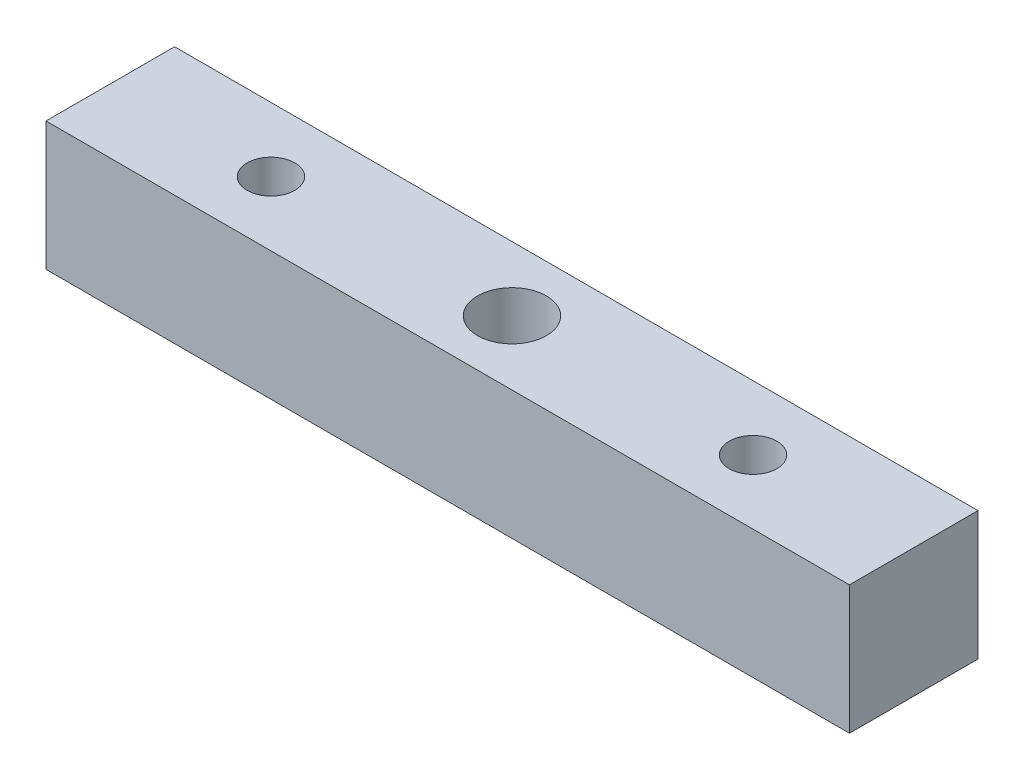
SolidWorks part; units mm, degrees
material "7075-T6 (SN)"
ref_plane "Front Plane" through (0, 0, 0) normal (0, 0, 1) x (1, 0, 0)
ref_plane "Top Plane" through (0, 0, 0) normal (0, 1, 0) x (1, 0, 0)
ref_plane "Right Plane" through (0, 0, 0) normal (1, 0, 0) x (0, 0, -1)
sketch "Sketch1" plane through (0, 0, 0) normal (0, 1, 0) x (1, 0, 0)
  line L1 (-25, 4) -> (25, 4)
  line L2 (-25, 4) -> (-25, -4)
  line L3 (-25, -4) -> (25, -4)
  line L4 (25, 4) -> (25, -4)
  line L5 (-25, 4) -> (25, -4) construction
  line L6 (-25, -4) -> (25, 4) construction
  point P0 (0, 0)
  dimension "D1" = 8
  dimension "D2" = 50
extrude "Boss-Extrude1" add sketch "Sketch1" along normal blind 8
sketch "Sketch2" plane through (0, 8, 0) normal (0, 1, 0) x (1, 0, 0)
  circle A0 centre (0, 0) radius 2.145
  circle A1 centre (-15, 0) radius 1.485
  circle A2 centre (15, 0) radius 1.485
  point P7 (-14.7993, -2.4456)
  point P8 (0, 0)
  point P9 (0, 0)
  dimension "D1" = 4.29
  dimension "D4" = 2.97
  dimension "D2" = 15
  dimension "D3" = 15
extrude "Cut-Extrude1" cut sketch "Sketch2" against normal blind 8
